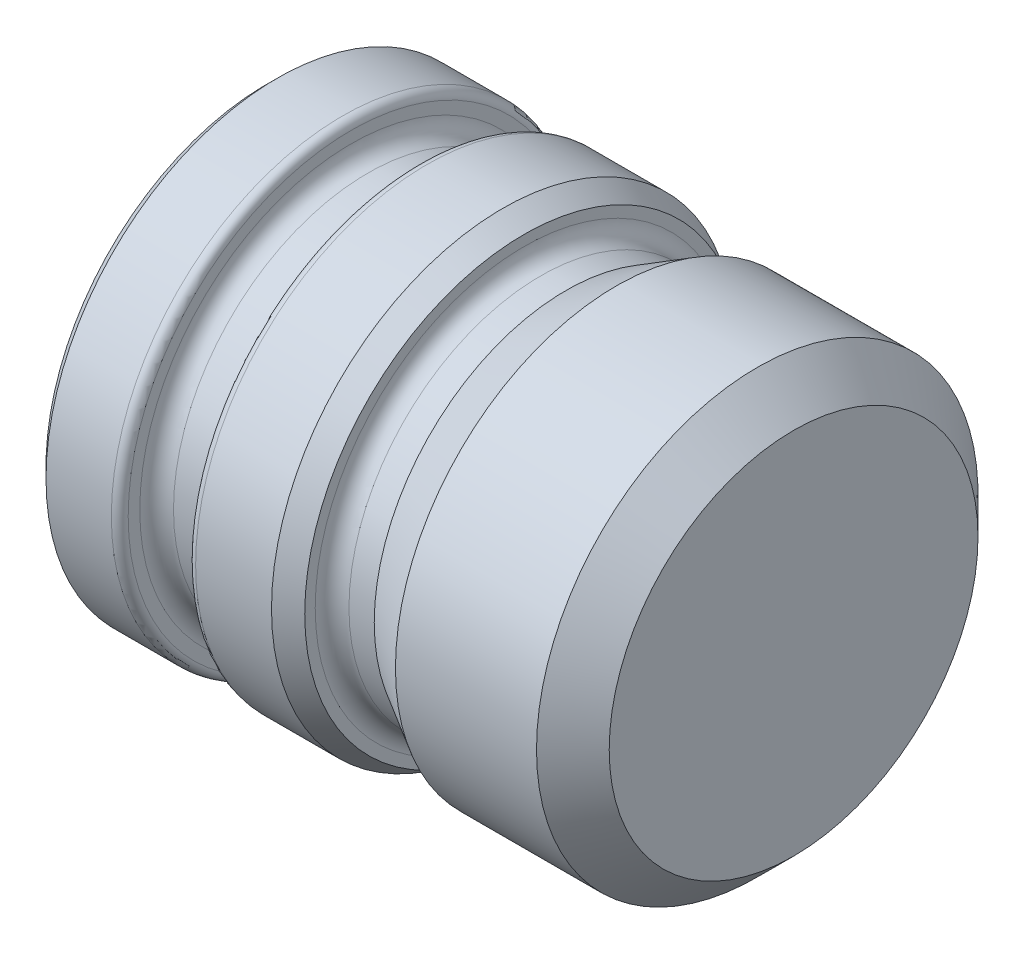
SolidWorks part; units mm, degrees
material "AISI 1045"
ref_plane "Front Plane" through (0, 0, 0) normal (0, 0, 1) x (1, 0, 0)
ref_plane "Top Plane" through (0, 0, 0) normal (0, 1, 0) x (1, 0, 0)
ref_plane "Right Plane" through (0, 0, 0) normal (1, 0, 0) x (0, 0, -1)
sketch "Sketch1" plane through (0, 0, 0) normal (0, 0, 1) x (1, 0, 0)
  line L0 (0, 0) -> (0, 8.75)
  line L1 (0, 8.75) -> (-1.725, 10.475)
  line L2 (-1.725, 10.475) -> (-8.4184, 10.475)
  line L3 (-8.4184, 10.475) -> (-10.8, 9.1)
  line L4 (-10.8, 9.1) -> (-12, 9.1)
  line L5 (-12.8, 9.9) -> (-12.8, 10.975)
  line L6 (-12.8, 10.975) -> (-17.4, 10.975)
  line L7 (-17.8, 10.575) -> (-17.8, 10.025)
  line L8 (-18.6, 9.225) -> (-20.2, 9.225)
  line L9 (-21, 10.025) -> (-21, 10.575)
  line L10 (-21.4, 10.975) -> (-25, 10.975)
  line L11 (-25, 10.975) -> (-25, 0)
  line L12 (-25, 0) -> (0, 0)
  line L13 (0, 0) -> (15.3627, 0) construction
  arc A0 (-17.8, 10.025) -> (-18.6, 9.225) centre (-18.6, 10.025) cw
  arc A1 (-20.2, 9.225) -> (-21, 10.025) centre (-20.2, 10.025) cw
  arc A2 (-17.4, 10.975) -> (-17.8, 10.575) centre (-17.4, 10.575) ccw
  arc A3 (-21, 10.575) -> (-21.4, 10.975) centre (-21.4, 10.575) ccw
  arc A4 (-12, 9.1) -> (-12.8, 9.9) centre (-12, 9.9) cw
  point P17 (-17.8, 9.225)
  point P20 (-21, 9.225)
  dimension "D13" = 0.8
  dimension "D14" = 0.4
  dimension "D15" = 0.8
  dimension "D1" = 25
  dimension "D2" = 21.95
  dimension "D3" = 18.45
  dimension "D4" = 3.2
  dimension "D5" = 4
  dimension "D6" = 12.8
  dimension "D7" = 20.95
  dimension "D8" = 18.2
  dimension "D9" = 30
  dimension "D10" = 2
  dimension "D11" = 45
  dimension "D12" = 17.5
revolve "Revolve1" add sketch "Sketch1" angle 360 about L13
cosmetic thread "Cosmetic Thread1" parameters "D1"=10.8, "D2"=19.5
sketch "Sketch2" plane through (-25, 0, 0) normal (-1, 0, 0) x (0, 0, 1)
  line L1 (-5, 5) -> (5, 5)
  line L2 (-5, 5) -> (-5, -5)
  line L3 (-5, -5) -> (5, -5)
  line L4 (5, 5) -> (5, -5)
  dimension "D1" = 10
  dimension "D2" = 10
  dimension "D3" = 5
  dimension "D4" = 5
extrude "Cut-Extrude1" cut sketch "Sketch2" against normal blind 10
chamfer "Chamfer2" distance 0.5 angle 45 1 edges at (-25, 0, 10.975)
chamfer "Chamfer3" distance 1 angle 30 1 edges at (-12.8, 0, 10.975)
sketch "Sketch3" plane through (-25, 0, 0) normal (-1, 0, 0) x (0, 0, 1)
  line L0 (0, 0) -> (12.8316, 0) construction
  line L1 (0, 0) -> (0, 7.4258) construction
  line L2 (5, 5) -> (-5, 5) construction
  circle A0 centre (3.8, 3.8) radius 1.75
  circle A1 centre (-3.8, 3.8) radius 1.75
  circle A2 centre (3.8, -3.8) radius 1.75
  circle A3 centre (-3.8, -3.8) radius 1.75
  dimension "D3" = 3.5
  dimension "D1" = 7.6
  dimension "D2" = 7.6
extrude "Cut-Extrude2" cut sketch "Sketch3" against normal up to surface (10 mm away) up to face at (-15, 0, 0)
chamfer "Chamfer4" distance 0.5 angle 45 8 edges at (-25, -5, 0) (-25, 0, 5) (-25, 5, 0) (-25, 0, -5) (-25, -5.0374, -5.0374) (-25, -5.0374, 5.0374) (-25, 5.0374, 5.0374) (-25, 5.0374, -5.0374)
sketch "Sketch4" plane through (-25, 0, 0) normal (-1, 0, 0) x (0, 0, 1)
  line L0 (-3.4805, 7.0929) -> (3.5995, 7.0929) construction
  line L1 (-5.6848, -8.0784) -> (5.337, -8.0784) construction
  text T1 "150 221 58" font "Century Gothic" height 1.5
  line B0 (1.3723, 6.0464) -> (-0.5887, 6.0464)
  line B1 (1.0819, 6.4462) -> (-0.3614, 6.4462)
  line B2 (-0.5546, 6.1064) -> (-0.3955, 6.3862)
  line B3 (0.1661, 8.113) -> (-0.176, 8.113)
  line B4 (-0.5887, 9.4713) -> (0.1661, 8.113)
  line B5 (1.0819, 6.4462) -> (0.3712, 7.7346)
  line B6 (1.9488, 7.7346) -> (2.1281, 7.4247)
  line B7 (0.3737, 9.4713) -> (-0.5887, 9.4713)
  line B8 (1.7425, 8.113) -> (1.9488, 7.7346)
  line B9 (1.7425, 8.113) -> (1.2242, 8.9869)
  line B10 (-0.5887, 6.0464) -> (-2.0872, 6.0464)
  line B11 (-1.2448, 7.5279) -> (-2.0872, 6.0464)
  line B12 (1.8614, 7.7948) -> (1.7083, 8.053)
  line B13 (0.3737, 9.4113) -> (-0.4868, 9.4113)
  line B14 (-0.4868, 9.4113) -> (0.2347, 8.113)
  line B15 (-0.176, 8.053) -> (1.7083, 8.053)
  line B16 (-1.1934, 7.4969) -> (-1.9841, 6.1064)
  line B17 (-0.6236, 6.1064) -> (-1.9841, 6.1064)
  line B18 (0.3364, 7.7948) -> (1.8614, 7.7948)
  line B19 (-0.6236, 6.1064) -> (0.3364, 7.7948)
  line B20 (1.8795, 7.7346) -> (2.0768, 7.3935)
  line B21 (1.3723, 6.1064) -> (-0.5546, 6.1064)
  line B22 (0.2347, 8.113) -> (1.6727, 8.113)
  line B23 (1.6727, 8.113) -> (1.1726, 8.9563)
  line B24 (1.1835, 6.3862) -> (-0.3955, 6.3862)
  line B25 (1.1835, 6.3862) -> (0.4397, 7.7346)
  line B26 (0.4397, 7.7346) -> (1.8795, 7.7346)
  line B27 (-0.3614, 6.4462) -> (0.3712, 7.7346)
  arc B28 (1.2242, 8.9869) -> (0.3737, 9.4713) centre (0.3737, 8.4825) ccw
  arc B29 (1.3723, 6.0464) -> (2.1281, 7.4247) centre (1.3723, 6.9428) ccw
  arc B30 (-0.176, 8.113) -> (-1.2448, 7.5279) centre (-0.176, 6.8442) ccw
  arc B31 (1.1726, 8.9563) -> (0.3737, 9.4113) centre (0.3737, 8.4825) ccw
  arc B32 (-0.176, 8.053) -> (-1.1934, 7.4969) centre (-0.176, 6.8442) ccw
  arc B33 (1.3723, 6.1064) -> (2.0768, 7.3935) centre (1.3723, 6.9428) ccw
  dimension "D1" = 7.0929
  dimension "D2" = 8.0784
sketch_block_instance "SKETCH LOGO-1"
sketch_block "SKETCH LOGO" parameters "D1"=29.059, "D2"=11.4163, "D3"=29.624, "D4"=6.8884
extrude "Cut-Extrude3" cut sketch "Sketch4" against normal blind 0.01
equation "\"D1@Sketch3\" = \"D2@Sketch3\""
